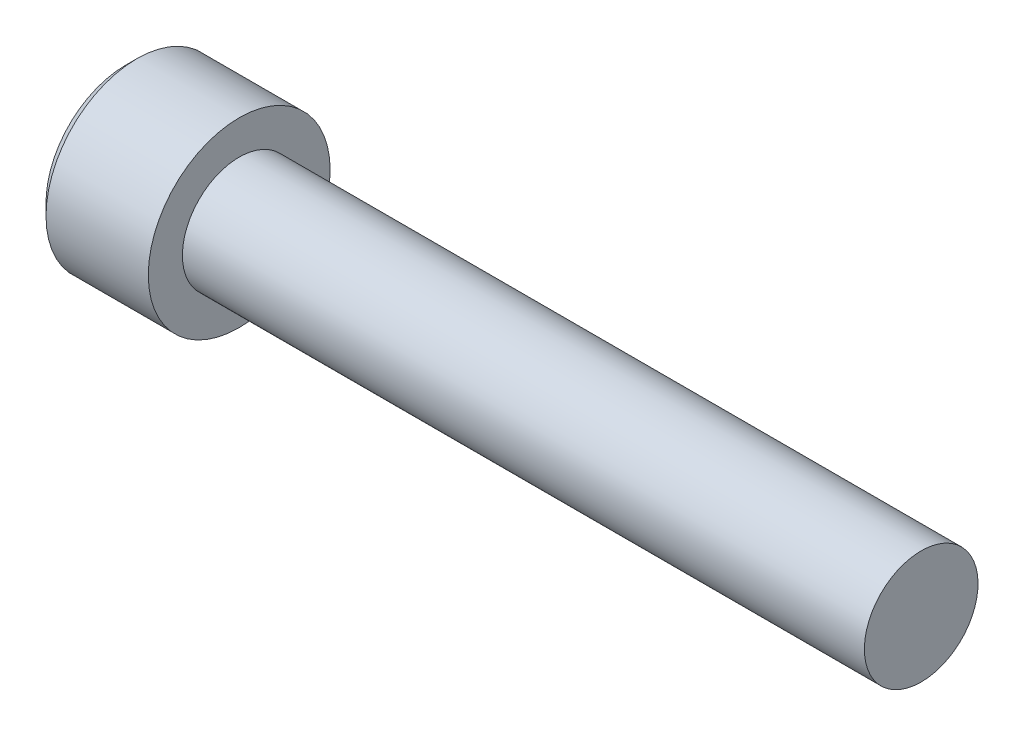
SolidWorks part; units mm, degrees
material "SCM435"
ref_plane "Front Plane" through (0, 0, 0) normal (0, 0, 1) x (1, 0, 0)
ref_plane "Top Plane" through (0, 0, 0) normal (0, 1, 0) x (1, 0, 0)
ref_plane "Right Plane" through (0, 0, 0) normal (1, 0, 0) x (0, 0, -1)
sketch "Sketch1" plane through (0, 0, 0) normal (0, 0, 1) x (1, 0, 0)
  line L0 (-10, 0) -> (60, 0) construction
  line L1 (0, 5) -> (60, 5)
  line L3 (-10, 0) -> (60, 0)
  line L4 (60, 5) -> (60, 0)
  line L6 (0, 5) -> (0, 8)
  line L7 (0, 8) -> (-10, 8)
  line L8 (-10, 0) -> (-10, 8)
  dimension "L" = 60
  dimension "M" = 10
  dimension "E" = 10
  dimension "A" = 16
revolve "Revolve1" add sketch "Sketch1" about L0
cosmetic thread "Thread1" parameters "L_s"=32, "ATD"=8.376
sketch "Sketch2" plane through (0, 0, 0) normal (0, 0, 1) x (1, 0, 0)
  line L0 (-10, 4) -> (-5, 4)
  line L1 (-10, 0) -> (-10, 8) construction
  line L2 (-5, 4) -> (-2.5966, 0)
  line L3 (-10, 0) -> (60, 0) construction
  line L4 (-2.5966, 0) -> (-10, 0) construction
  line L5 (-10, 0) -> (-10, 4)
  line L6 (-2.5966, 0) -> (-10, 0)
  dimension "FIX_2" = 59
  dimension "MSM_1" = 5
revolve "Cut-Revolve1" cut sketch "Sketch2" about L4
sketch "Sketch3" plane through (-10, 0, 0) normal (-1, 0, 0) x (0, 0, 1)
  line L0 (0, -8.8) -> (0, 8.8) construction
  line L1 (4, 2.3094) -> (0, 4.6188)
  line L2 (0, 4.6188) -> (-4, 2.3094)
  line L3 (-4, 2.3094) -> (-4, -2.3094)
  line L4 (-4, -2.3094) -> (0, -4.6188)
  line L5 (0, -4.6188) -> (4, -2.3094)
  line L6 (4, -2.3094) -> (4, 2.3094)
  circle A0 centre (0, 0) radius 4 construction
extrude "Cut-Extrude1" cut sketch "Sketch3" against normal blind 5
chamfer "Chamfer1" distance 1 1 edges at (-10, -8, 0)
